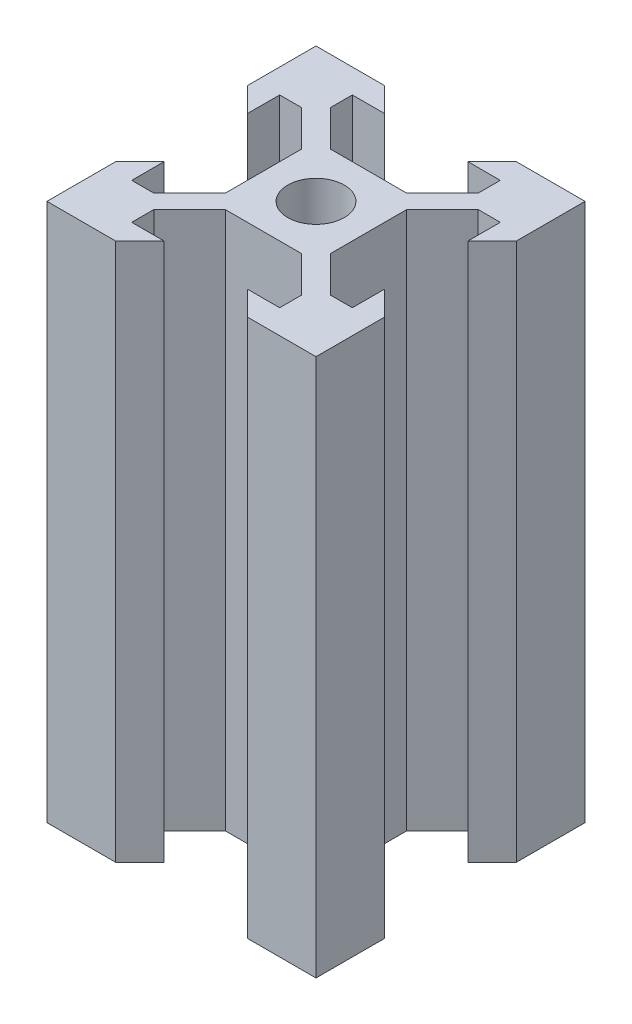
SolidWorks part; units mm, degrees
ref_plane "Front Plane" through (0, 0, 0) normal (0, 0, 1) x (1, 0, 0)
ref_plane "Top Plane" through (0, 0, 0) normal (0, 1, 0) x (1, 0, 0)
ref_plane "Right Plane" through (0, 0, 0) normal (1, 0, 0) x (0, 0, -1)
sketch "Sketch1" plane through (0, 0, 0) normal (0, 1, 0) x (1, 0, 0)
  line L0 (3.9007, 2.84) -> (2.84, 3.9007) construction
  line L1 (-10, -10) -> (10, -10) construction
  line L2 (-10, -10) -> (-10, 10) construction
  line L3 (-10, 10) -> (10, 10) construction
  line L4 (10, -10) -> (10, 10) construction
  line L5 (-10, -10) -> (10, 10) construction
  line L6 (-10, 10) -> (10, -10) construction
  line L7 (-2.84, -2.84) -> (2.84, -2.84) construction
  line L8 (-2.84, -2.84) -> (-2.84, 2.84) construction
  line L9 (-2.84, 2.84) -> (2.84, 2.84) construction
  line L10 (2.84, -2.84) -> (2.84, 2.84) construction
  line L11 (-2.84, -2.84) -> (2.84, 2.84) construction
  line L12 (-2.84, 2.84) -> (2.84, -2.84) construction
  line L13 (2.84, -3.9007) -> (3.9007, -2.84) construction
  line L14 (-3.9007, -2.84) -> (-2.84, -3.9007) construction
  line L15 (-2.84, 3.9007) -> (-3.9007, 2.84) construction
  line L16 (-3.1, 10) -> (3.1, 10) construction
  line L17 (-3.1, 10) -> (-3.1, 8.2) construction
  line L18 (-3.1, 8.2) -> (-4.9, 10)
  line L19 (3.1, 8.2) -> (3.1, 10) construction
  line L20 (-3.1, 8.2) -> (-8.2, 8.2) construction
  line L21 (-2.84, 3.9007) -> (-7.1393, 8.2) construction
  line L22 (-5.4993, 8.2) -> (-5.4993, 6.56)
  line L23 (-4.9, 10) -> (-10, 10)
  line L24 (-3.9007, -3.9007) -> (3.9007, -3.9007) construction
  line L25 (-3.9007, -3.9007) -> (-3.9007, 3.9007) construction
  line L26 (-3.9007, 3.9007) -> (3.9007, 3.9007) construction
  line L27 (3.9007, -3.9007) -> (3.9007, 3.9007) construction
  line L28 (-3.9007, -3.9007) -> (3.9007, 3.9007) construction
  line L29 (-3.9007, 3.9007) -> (3.9007, -3.9007) construction
  line L30 (-5.4993, 6.56) -> (-2.84, 3.9007)
  line L31 (-2.84, 3.9007) -> (0, 3.9007)
  line L32 (-5.4993, 8.2) -> (-3.1, 8.2)
  line L33 (-3.9007, 2.84) -> (-3.9007, 0)
  line L34 (-6.56, 5.4993) -> (-3.9007, 2.84)
  line L35 (-8.2, 5.4993) -> (-6.56, 5.4993)
  line L36 (-8.2, 5.4993) -> (-8.2, 3.1)
  line L37 (-8.2, 3.1) -> (-10, 4.9)
  line L38 (-10, 4.9) -> (-10, 10)
  line L39 (2.84, 3.9007) -> (0, 3.9007)
  line L40 (5.4993, 6.56) -> (2.84, 3.9007)
  line L41 (5.4993, 8.2) -> (5.4993, 6.56)
  line L42 (5.4993, 8.2) -> (3.1, 8.2)
  line L43 (3.1, 8.2) -> (4.9, 10)
  line L44 (4.9, 10) -> (10, 10)
  line L45 (10, 4.9) -> (10, 10)
  line L46 (8.2, 3.1) -> (10, 4.9)
  line L47 (8.2, 5.4993) -> (8.2, 3.1)
  line L48 (8.2, 5.4993) -> (6.56, 5.4993)
  line L49 (6.56, 5.4993) -> (3.9007, 2.84)
  line L50 (3.9007, 2.84) -> (3.9007, 0)
  line L51 (3.9007, -2.84) -> (3.9007, 0)
  line L52 (6.56, -5.4993) -> (3.9007, -2.84)
  line L53 (8.2, -5.4993) -> (6.56, -5.4993)
  line L54 (8.2, -5.4993) -> (8.2, -3.1)
  line L55 (8.2, -3.1) -> (10, -4.9)
  line L56 (10, -4.9) -> (10, -10)
  line L57 (4.9, -10) -> (10, -10)
  line L58 (3.1, -8.2) -> (4.9, -10)
  line L59 (5.4993, -8.2) -> (3.1, -8.2)
  line L60 (5.4993, -8.2) -> (5.4993, -6.56)
  line L61 (5.4993, -6.56) -> (2.84, -3.9007)
  line L62 (2.84, -3.9007) -> (0, -3.9007)
  line L63 (-2.84, -3.9007) -> (0, -3.9007)
  line L64 (-5.4993, -6.56) -> (-2.84, -3.9007)
  line L65 (-5.4993, -8.2) -> (-5.4993, -6.56)
  line L66 (-5.4993, -8.2) -> (-3.1, -8.2)
  line L67 (-3.1, -8.2) -> (-4.9, -10)
  line L68 (-4.9, -10) -> (-10, -10)
  line L69 (-10, -4.9) -> (-10, -10)
  line L70 (-8.2, -3.1) -> (-10, -4.9)
  line L71 (-8.2, -5.4993) -> (-8.2, -3.1)
  line L72 (-8.2, -5.4993) -> (-6.56, -5.4993)
  line L73 (-6.56, -5.4993) -> (-3.9007, -2.84)
  line L74 (-3.9007, -2.84) -> (-3.9007, 0)
  circle A0 centre (0, 0) radius 2.1
  circle A1 centre (0, 0) radius 2.1
  circle A2 centre (0, 0) radius 2.1
  circle A3 centre (0, 0) radius 2.1
  point P0 (0, 0)
  point P15 (3.3703, 3.3703)
  point P27 (0, 0)
  point P28 (0, 10)
  point P87 (0, 0)
  dimension "D2" = 4.2
  dimension "D1" = 20
  dimension "D3" = 5.68
  dimension "D4" = 1.5
  dimension "D6" = 6.2
  dimension "D7" = 1.8
  dimension "D8" = 45
  dimension "D9" = 1.64
  dimension "D10" = 4
  dimension "D11" = 90
  dimension "D12" = 1.64
  dimension "D13" = 20
  dimension "D14" = 1.5
  dimension "D15" = 5.68
  dimension "D16" = 6.2
  dimension "D17" = 1.8
  dimension "D5" = 4
extrude "Boss-Extrude1" add sketch "Sketch1" along normal blind 40 contours L74 L73 L72 L71 L70 L69 L68 L67 L66 L65 L64 L63 L62 L61 L60 L59 L58 L57 L56 L55 L54 L53 L52 L51 L50 L49 L48 L47 L46 L45 L44 L43 L42 L41 L40 L39 L31 L30 L22 L32 L18 L23 L38 L37 L36 L35 L34 L33 A0
